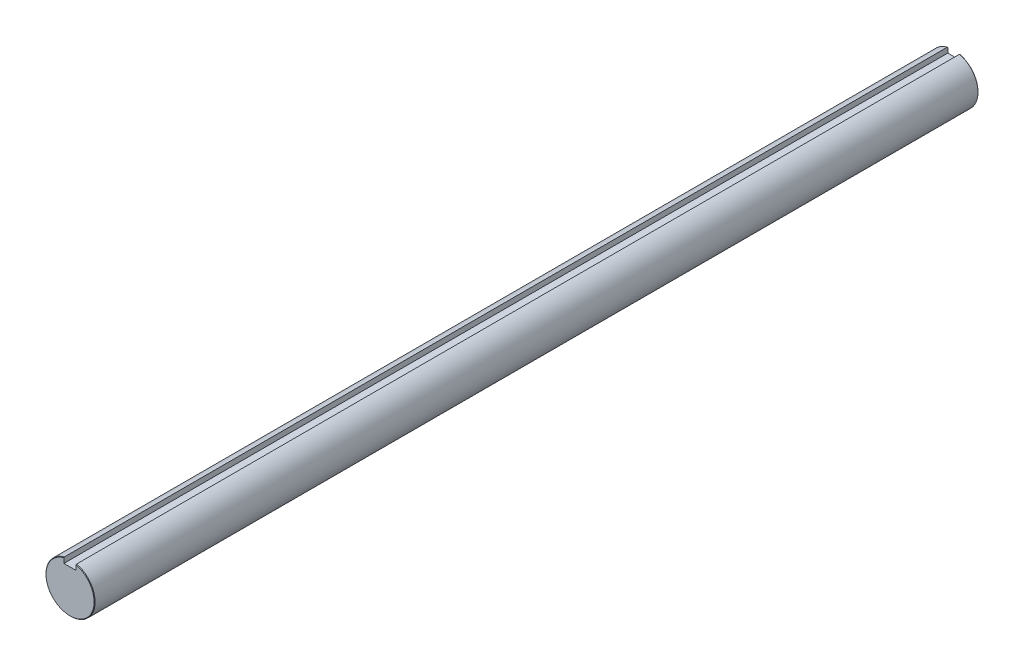
SolidWorks part; units mm, degrees
ref_plane "Front Plane" through (0, 0, 0) normal (0, 0, 1) x (1, 0, 0)
ref_plane "Top Plane" through (0, 0, 0) normal (0, 1, 0) x (1, 0, 0)
ref_plane "Right Plane" through (0, 0, 0) normal (1, 0, 0) x (0, 0, -1)
sketch "Sketch1" plane through (0, 0, 0) normal (1, 0, 0) x (0, 0, -1)
  line L0 (0, 0) -> (0, 6.35) construction
  line L1 (-114.3, 6.35) -> (114.3, 6.35)
  line L2 (-114.3, 6.35) -> (-114.3, -6.35)
  line L3 (-114.3, -6.35) -> (114.3, -6.35)
  line L4 (114.3, 6.35) -> (114.3, -6.35)
  line L5 (-114.3, 6.35) -> (114.3, -6.35) construction
  line L6 (-114.3, -6.35) -> (114.3, 6.35) construction
  line L7 (0, 0) -> (0, -6.35) construction
  line L8 (114.3, 6.35) -> (-114.3, 6.35) construction
  point P0 (0, 0)
  point P8 (-99.695, 6.35)
  point P10 (99.695, 6.35)
  point P11 (-94.8267, -6.35)
  point P12 (97.4356, -6.35)
  point P15 (0, 6.35)
  dimension "Diameter" = 12.7
  dimension "Length" = 228.6
  dimension "D1" = 14.605
  dimension "D2" = 14.605
  dimension "D3" = 19.4733
  dimension "D4" = 16.8644
  dimension "Key Length" = 228.6
sketch "Sketch2" plane through (0, 0, 0) normal (0, 0, 1) x (1, 0, 0)
  line L0 (0, 0) -> (0, 6.35) construction
  line L2 (1.5875, 4.7498) -> (-1.5875, 4.7498)
  line L3 (1.5875, 4.7498) -> (1.5875, 6.35)
  line L4 (1.5875, 6.35) -> (-1.5875, 6.35)
  line L5 (-1.5875, 4.7498) -> (-1.5875, 6.35)
  line L6 (1.5875, 4.7498) -> (-1.5875, 6.35) construction
  line L7 (1.5875, 6.35) -> (-1.5875, 4.7498) construction
  circle A0 centre (0, 0) radius 6.35
  point P3 (0, 5.5499)
  dimension "Keyway Width" = 3.175
  dimension "Keyway Depth" = 1.6002
sketch "Sketch3" plane through (0, 0, 0) normal (0, 0, 1) x (1, 0, 0)
  line L1 (-1.5875, 4.7498) -> (-1.5875, 6.35) construction
  line L2 (1.5875, 4.7498) -> (-1.5875, 4.7498) construction
  line L3 (1.5875, 4.7498) -> (1.5875, 6.35) construction
  line L5 (-1.5875, 4.7498) -> (-1.5875, 6.1484)
  line L6 (1.5875, 4.7498) -> (-1.5875, 4.7498)
  line L7 (1.5875, 4.7498) -> (1.5875, 6.1484)
  arc A1 (-1.5875, 6.1484) -> (1.5875, 6.1484) centre (0, 0) ccw
  circle A2 centre (0, 0) radius 6.35 construction
extrude "Boss-Extrude1" add sketch "Sketch3" along normal up to vertex (114.3 mm away) and the other way up to vertex (114.3 mm away) up to point (0, 6.35, 114.3) other way up to point (0, 6.35, -114.3)
chamfer "Chamfer1" distance 0.127 angle 45 2 edges at (0, -6.35, 114.3) (0, -6.35, -114.3)
equation "\"D2@Sketch1\"=1.15*\"Diameter@Sketch1\""
equation "\"D1@Sketch1\"=\"D2@Sketch1\""
equation "\"D3@Sketch1\"=\"D2@Sketch1\"*4/3"
equation "\"D4@Sketch1\"=\"D2@Sketch1\"/(tan(.5236*180/pi)*2)*4/3"
equation "\"D1@Chamfer1\"=\"Diameter@Sketch1\"*.01"
equation "\"Key Length@Sketch1\"=\"Length@Sketch1\""
